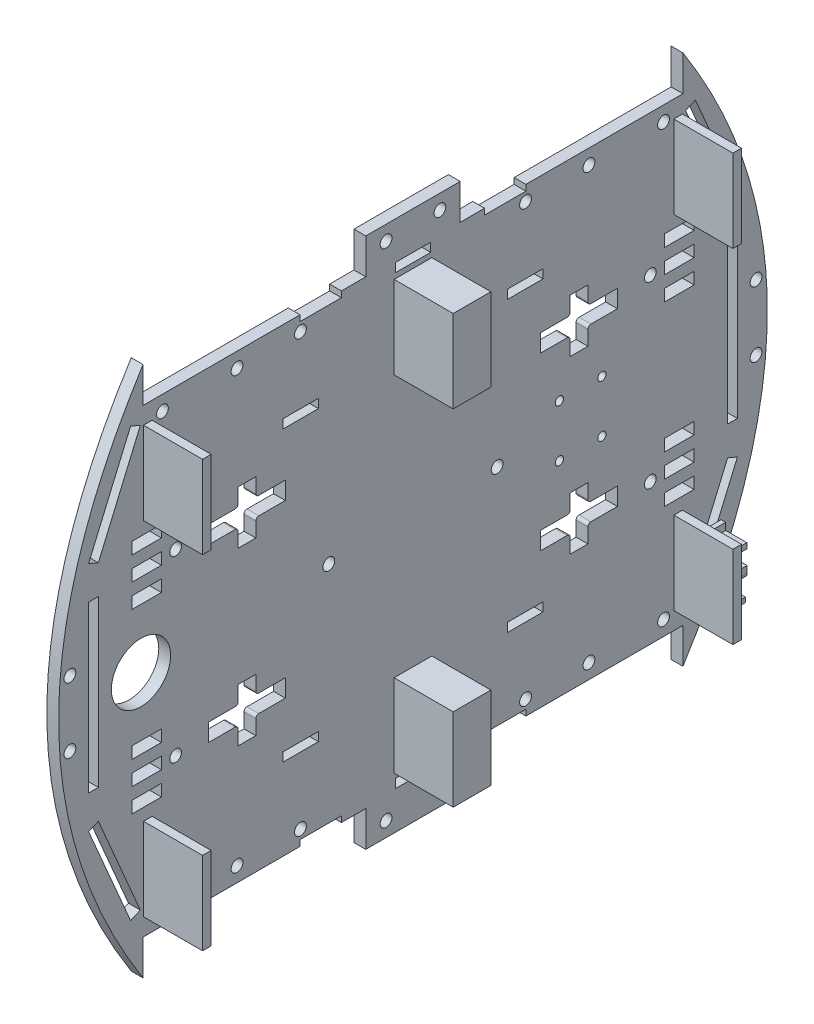
SolidWorks part; units mm, degrees
ref_plane "Front Plane" through (0, 0, 0) normal (0, 0, 1) x (1, 0, 0)
ref_plane "Top Plane" through (0, 0, 0) normal (0, 1, 0) x (1, 0, 0)
ref_plane "Right Plane" through (0, 0, 0) normal (1, 0, 0) x (0, 0, -1)
sketch "Sketch2" plane through (0, 0, 0) normal (1, 0, 0) x (0, 0, -1)
  line L0 (0, 0) -> (-14.2457, 0)
  line L1 (-120, 0) -> (-120, 90)
  line L2 (-120, 90) -> (-105.7002, 90)
  line L3 (0, 90) -> (0, 0)
  line L4 (-120, 45) -> (0, 45) construction
  line L5 (-59.9729, 90) -> (-59.9729, 0) construction
  line L6 (-105.7002, 90) -> (-105.7002, 84)
  line L7 (-105.7002, 84) -> (-79.1012, 84)
  line L8 (-14.2457, 90) -> (-14.2457, 84)
  line L9 (-14.2457, 0) -> (-14.2457, 6)
  line L10 (-105.7002, 6) -> (-79.1012, 6)
  line L11 (-105.7002, 0) -> (-105.7002, 6)
  line L12 (-67.9729, 84) -> (-67.9729, 90)
  line L13 (-67.9729, 90) -> (-51.9729, 90)
  line L14 (-51.9729, 90) -> (-51.9729, 84)
  line L15 (-51.9729, 0) -> (-51.9729, 6)
  line L16 (-120, 0) -> (-105.7002, 0)
  line L17 (-67.9729, 6) -> (-67.9729, 0)
  line L18 (-67.9729, 90) -> (-51.9729, 90)
  line L19 (-14.2457, 90) -> (0, 90)
  line L20 (-105.7002, 0) -> (-120, 0)
  line L21 (-67.9729, 0) -> (-51.9729, 0)
  line L22 (-51.9729, 0) -> (-67.9729, 0)
  line L23 (-14.2457, 0) -> (0, 0)
  line L24 (-51.9729, 6) -> (-47.8447, 6)
  line L25 (-51.9729, 84) -> (-47.8447, 84)
  line L26 (-72.1012, 84) -> (-72.1012, 83)
  line L27 (-72.1012, 83) -> (-79.1012, 83)
  line L28 (-79.1012, 83) -> (-79.1012, 84)
  line L29 (-47.8447, 84) -> (-47.8447, 83)
  line L30 (-47.8447, 83) -> (-40.8447, 83)
  line L31 (-40.8447, 83) -> (-40.8447, 84)
  line L32 (-40.8447, 7) -> (-40.8447, 6)
  line L33 (-47.8447, 7) -> (-40.8447, 7)
  line L34 (-47.8447, 6) -> (-47.8447, 7)
  line L35 (-79.1012, 7) -> (-79.1012, 6)
  line L36 (-72.1012, 7) -> (-79.1012, 7)
  line L37 (-72.1012, 6) -> (-72.1012, 7)
  line L38 (-72.1012, 84) -> (-67.9729, 84)
  line L39 (-40.8447, 84) -> (-14.2457, 84)
  line L40 (-72.1012, 6) -> (-67.9729, 6)
  line L41 (-40.8447, 6) -> (-14.2457, 6)
  spline S0 degree 2 poles (-14.2457, 90) (14.354, 45) (-14.2457, 0) knots 0 0 0 1 1 1
  spline S1 degree 2 poles (-105.7002, 90) (-134.2998, 45) (-105.7002, 0) knots 0 0 0 1 1 1
  point P17 (-59.9729, 84)
  dimension "D7" = 95.7362
  dimension "D1" = 120
  dimension "D2" = 90
  dimension "D3" = 8
  dimension "D4" = 8
  dimension "D5" = 6
  dimension "D6" = 1
  dimension "D8" = 7
extrude "Boss-Extrude1" add sketch "Sketch2" along normal blind 2 contours L6 S1 L11 L10 L35 L36 L37 L40 L17 L21 L15 L24 L34 L33 L32 L41 L9 S0 L3 L8 L39 L31 L30 L29 L25 L14 L13 L12 L38 L26 L27 L28 L7
sketch "Sketch3" plane through (2, 0, 0) normal (1, 0, 0) x (0, 0, -1)
  line L0 (-105.6201, 81.0571) -> (-105.6201, 67.0571)
  line L1 (-105.6201, 67.0571) -> (-104.1642, 67.0571)
  line L2 (-104.1642, 67.0571) -> (-104.1642, 81.0571)
  line L3 (-104.1642, 81.0571) -> (-105.6201, 81.0571)
  line L4 (-120, 45) -> (1.0597, 45) construction
  line L5 (-59.9729, 90) -> (-59.9729, 45) construction
  line L6 (-67.9729, 90) -> (-51.9729, 90) construction
  line L7 (-14.3257, 67.0571) -> (-15.7817, 67.0571)
  line L8 (-15.7817, 81.0571) -> (-14.3257, 81.0571)
  line L9 (-15.7817, 67.0571) -> (-15.7817, 81.0571)
  line L10 (-14.3257, 81.0571) -> (-14.3257, 67.0571)
  line L11 (-14.3257, 8.9429) -> (-14.3257, 22.9429)
  line L12 (-15.7817, 22.9429) -> (-15.7817, 8.9429)
  line L13 (-15.7817, 8.9429) -> (-14.3257, 8.9429)
  line L14 (-14.3257, 22.9429) -> (-15.7817, 22.9429)
  line L15 (-104.1642, 8.9429) -> (-105.6201, 8.9429)
  line L16 (-104.1642, 22.9429) -> (-104.1642, 8.9429)
  line L17 (-105.6201, 22.9429) -> (-104.1642, 22.9429)
  line L18 (-105.6201, 8.9429) -> (-105.6201, 22.9429)
  parabola Q0 (-105.7002, 90) -> (-105.7002, 0) focus (-84.5975, 45) apex (-120, 45) construction
  dimension "D1" = 14
extrude "Boss-Extrude2" add sketch "Sketch3" along normal blind 10
sketch "Sketch5" plane through (2, 0, 0) normal (1, 0, 0) x (0, 0, -1)
  line L0 (-56.7817, 8.7817) -> (-63.1642, 8.7817)
  line L1 (-63.1642, 8.7817) -> (-63.1642, 22.7817)
  line L2 (-63.1642, 22.7817) -> (-56.7817, 22.7817)
  line L3 (-56.7817, 22.7817) -> (-56.7817, 8.7817)
  line L4 (-104.1642, 8.9429) -> (-104.1642, 22.9429) construction
  line L5 (-15.7817, 22.9429) -> (-15.7817, 8.9429) construction
  line L6 (0, 45) -> (-130.9213, 45) construction
  line L7 (0, 47.7682) -> (0, 42.2318) construction
  line L14 (-56.7817, 67.2183) -> (-56.7817, 81.2183)
  line L15 (-63.1642, 67.2183) -> (-56.7817, 67.2183)
  line L16 (-63.1642, 81.2183) -> (-63.1642, 67.2183)
  line L17 (-56.7817, 81.2183) -> (-63.1642, 81.2183)
  dimension "D1" = 41
  dimension "D2" = 41
  dimension "D3" = 14
extrude "Boss-Extrude3" add sketch "Sketch5" along normal blind 10
sketch "Sketch6" plane through (0, 0, 0) normal (1, 0, 0) x (0, 0, -1)
  line L0 (-59.9729, 90) -> (-59.9729, 0) construction
  line L1 (-67.9729, 90) -> (-51.9729, 90) construction
  line L2 (-67.9729, 0) -> (-51.9729, 0) construction
  line L3 (0, 45) -> (-120, 45) construction
  line L4 (0, 47.7682) -> (0, 42.2318) construction
  line L5 (-88.1012, 84) -> (-88.1012, 69.2326) construction
  line L6 (-105.7002, 84) -> (-79.1012, 84) construction
  line L7 (-86.6012, 64) -> (-89.6012, 64)
  line L8 (-89.6012, 64) -> (-89.6012, 61.5)
  line L9 (-90.1012, 61) -> (-94.6012, 61)
  line L10 (-81.6012, 59.5) -> (-100.8376, 59.5) construction
  line L11 (-90.1012, 58) -> (-94.6012, 58)
  line L12 (-89.6012, 55) -> (-89.6012, 57.5)
  line L13 (-86.6012, 55) -> (-89.6012, 55)
  line L14 (-81.6012, 58) -> (-86.1012, 58)
  line L15 (-94.6012, 61) -> (-94.6012, 58)
  line L16 (-81.6012, 58) -> (-81.6012, 61)
  line L17 (-81.6012, 61) -> (-86.1012, 61)
  line L18 (-86.6012, 61.5) -> (-86.6012, 64)
  line L19 (-79.1012, 83) -> (-79.1012, 84) construction
  line L20 (-86.6012, 57.5) -> (-86.6012, 55)
  line L21 (-33.3447, 57.5) -> (-33.3447, 55)
  line L22 (-33.3447, 61.5) -> (-33.3447, 64)
  line L23 (-38.3447, 61) -> (-33.8447, 61)
  line L24 (-38.3447, 58) -> (-38.3447, 61)
  line L25 (-25.3447, 61) -> (-25.3447, 58)
  line L26 (-38.3447, 58) -> (-33.8447, 58)
  line L27 (-33.3447, 55) -> (-30.3447, 55)
  line L28 (-30.3447, 55) -> (-30.3447, 57.5)
  line L29 (-29.8447, 58) -> (-25.3447, 58)
  line L30 (-29.8447, 61) -> (-25.3447, 61)
  line L31 (-30.3447, 64) -> (-30.3447, 61.5)
  line L32 (-33.3447, 64) -> (-30.3447, 64)
  line L33 (-86.6012, 32.5) -> (-86.6012, 35)
  line L34 (-86.6012, 28.5) -> (-86.6012, 26)
  line L35 (-81.6012, 29) -> (-86.1012, 29)
  line L36 (-81.6012, 32) -> (-81.6012, 29)
  line L37 (-94.6012, 29) -> (-94.6012, 32)
  line L38 (-81.6012, 32) -> (-86.1012, 32)
  line L39 (-86.6012, 35) -> (-89.6012, 35)
  line L40 (-89.6012, 35) -> (-89.6012, 32.5)
  line L41 (-90.1012, 32) -> (-94.6012, 32)
  line L42 (-90.1012, 29) -> (-94.6012, 29)
  line L43 (-89.6012, 26) -> (-89.6012, 28.5)
  line L44 (-86.6012, 26) -> (-89.6012, 26)
  line L45 (-33.3447, 26) -> (-30.3447, 26)
  line L46 (-30.3447, 26) -> (-30.3447, 28.5)
  line L47 (-29.8447, 29) -> (-25.3447, 29)
  line L48 (-29.8447, 32) -> (-25.3447, 32)
  line L49 (-30.3447, 35) -> (-30.3447, 32.5)
  line L50 (-33.3447, 35) -> (-30.3447, 35)
  line L51 (-38.3447, 32) -> (-33.8447, 32)
  line L52 (-25.3447, 29) -> (-25.3447, 32)
  line L53 (-38.3447, 32) -> (-38.3447, 29)
  line L54 (-38.3447, 29) -> (-33.8447, 29)
  line L55 (-33.3447, 28.5) -> (-33.3447, 26)
  line L56 (-33.3447, 32.5) -> (-33.3447, 35)
  circle A0 centre (-106.0549, 45) radius 5.019
  arc A1 (-89.6012, 61.5) -> (-90.1012, 61) centre (-90.1012, 61.5) cw
  arc A2 (-90.1012, 58) -> (-89.6012, 57.5) centre (-90.1012, 57.5) cw
  arc A3 (-86.1012, 58) -> (-86.6012, 57.5) centre (-86.1012, 57.5) ccw
  arc A4 (-86.1012, 61) -> (-86.6012, 61.5) centre (-86.1012, 61.5) cw
  arc A5 (-33.8447, 61) -> (-33.3447, 61.5) centre (-33.8447, 61.5) ccw
  arc A6 (-33.8447, 58) -> (-33.3447, 57.5) centre (-33.8447, 57.5) cw
  arc A7 (-29.8447, 58) -> (-30.3447, 57.5) centre (-29.8447, 57.5) ccw
  arc A8 (-30.3447, 61.5) -> (-29.8447, 61) centre (-29.8447, 61.5) ccw
  arc A9 (-86.1012, 29) -> (-86.6012, 28.5) centre (-86.1012, 28.5) ccw
  arc A10 (-86.1012, 32) -> (-86.6012, 32.5) centre (-86.1012, 32.5) cw
  arc A11 (-90.1012, 32) -> (-89.6012, 32.5) centre (-90.1012, 32.5) ccw
  arc A12 (-89.6012, 28.5) -> (-90.1012, 29) centre (-90.1012, 28.5) ccw
  arc A13 (-30.3447, 28.5) -> (-29.8447, 29) centre (-29.8447, 28.5) cw
  arc A14 (-29.8447, 32) -> (-30.3447, 32.5) centre (-29.8447, 32.5) cw
  arc A15 (-33.8447, 32) -> (-33.3447, 32.5) centre (-33.8447, 32.5) ccw
  arc A16 (-33.8447, 29) -> (-33.3447, 28.5) centre (-33.8447, 28.5) cw
  circle A17 centre (-13.891, 45) radius 5.019
  parabola Q0 (-105.7002, 90) -> (-105.7002, 0) focus (-84.5975, 45) apex (-120, 45) construction
  point P38 (-89.6012, 61)
  point P41 (-89.6012, 58)
  point P44 (-86.6012, 58)
  point P47 (-86.6012, 61)
  point P68 (-33.3447, 61)
  point P69 (-33.3447, 58)
  point P70 (-30.3447, 58)
  point P71 (-30.3447, 61)
  point P92 (-86.6012, 29)
  point P93 (-86.6012, 32)
  point P94 (-89.6012, 32)
  point P95 (-89.6012, 29)
  point P116 (-30.3447, 29)
  point P117 (-30.3447, 32)
  point P118 (-33.3447, 32)
  point P119 (-33.3447, 29)
  dimension "D6" = 0.5
  dimension "D1" = 20
  dimension "D2" = 1.5
  dimension "D3" = 1.5
  dimension "D4" = 9
  dimension "D5" = 5
  dimension "D8" = 3
  dimension "D9" = 3
  dimension "D10" = 5
  dimension "D11" = 3
extrude "Cut-Extrude5" cut sketch "Sketch6" along normal blind 24
sketch "Sketch7" plane through (0, 0, 0) normal (1, 0, 0) x (0, 0, -1)
  line L0 (-107.8144, 82.0133) -> (-114.9272, 65.4166)
  line L1 (-114.9272, 65.4166) -> (-113.2739, 64.708)
  line L2 (-113.2739, 64.708) -> (-106.1611, 81.3048)
  line L3 (-106.1611, 81.3048) -> (-107.8144, 82.0133)
  line L4 (-114.9272, 59.7526) -> (-114.9272, 31.7526)
  line L5 (-114.9272, 31.7526) -> (-113.2739, 31.7526)
  line L6 (-113.2739, 31.7526) -> (-113.2739, 59.7526)
  line L7 (-113.2739, 59.7526) -> (-114.9272, 59.7526)
  line L8 (-119.996, 45.7526) -> (35.8922, 45.7526) construction
  line L9 (-107.8144, 9.492) -> (-114.9272, 26.0887)
  line L10 (-113.2739, 26.7972) -> (-106.1611, 10.2005)
  line L11 (-113.2739, 26.7972) -> (-114.9272, 26.0887)
  line L12 (-107.8144, 9.492) -> (-106.1611, 10.2005)
  line L13 (-59.9729, 90) -> (-59.9729, 70.4012) construction
  line L14 (-67.9729, 90) -> (-51.9729, 90) construction
  line L15 (-6.6719, 26.7972) -> (-13.7848, 10.2005)
  line L16 (-12.1315, 9.492) -> (-5.0186, 26.0887)
  line L17 (-5.0186, 59.7526) -> (-5.0186, 31.7526)
  line L18 (-6.6719, 31.7526) -> (-6.6719, 59.7526)
  line L19 (-12.1315, 82.0133) -> (-5.0186, 65.4166)
  line L20 (-6.6719, 64.708) -> (-13.7848, 81.3048)
  line L21 (-12.1315, 82.0133) -> (-13.7848, 81.3048)
  line L22 (-5.0186, 65.4166) -> (-6.6719, 64.708)
  line L23 (-5.0186, 59.7526) -> (-6.6719, 59.7526)
  line L24 (-5.0186, 26.0887) -> (-6.6719, 26.7972)
  line L25 (-12.1315, 9.492) -> (-13.7848, 10.2005)
  line L26 (-6.6719, 31.7526) -> (-5.0186, 31.7526)
  parabola Q0 (-105.7002, 90) -> (-105.7002, 0) focus (-84.5975, 45) apex (-120, 45) construction
  point P14 (-114.1006, 59.7526)
  dimension "D1" = 14
  dimension "D2" = 14
extrude "Cut-Extrude6" cut sketch "Sketch7" along normal blind 41
sketch "Sketch9" plane through (0, 0, 0) normal (1, 0, 0) x (0, 0, -1)
  line L0 (-59.9729, 90) -> (-59.9729, 25.6471) construction
  line L1 (-67.9729, 90) -> (-51.9729, 90) construction
  line L2 (0, 45) -> (-59.9729, 45) construction
  line L3 (0, 47.7682) -> (0, 42.2318) construction
  line L4 (-12.3575, 55) -> (-17.3575, 55)
  line L5 (-17.3575, 55) -> (-17.3575, 57)
  line L6 (-17.3575, 57) -> (-12.3575, 57)
  line L7 (-12.3575, 57) -> (-12.3575, 55)
  line L8 (-12.3552, 59) -> (-17.3575, 59)
  line L9 (-17.3575, 59) -> (-17.3575, 61)
  line L10 (-17.3575, 61) -> (-12.3552, 61)
  line L11 (-12.3552, 61) -> (-12.3552, 59)
  line L12 (-12.3552, 63) -> (-17.3575, 63)
  line L13 (-17.3575, 63) -> (-17.3575, 65)
  line L14 (-17.3575, 65) -> (-12.3552, 65)
  line L15 (-12.3552, 65) -> (-12.3552, 63)
  line L16 (-12.3552, 25) -> (-12.3552, 27)
  line L17 (-17.3575, 25) -> (-12.3552, 25)
  line L18 (-17.3575, 27) -> (-17.3575, 25)
  line L19 (-12.3552, 27) -> (-17.3575, 27)
  line L20 (-12.3552, 29) -> (-12.3552, 31)
  line L21 (-17.3575, 29) -> (-12.3552, 29)
  line L22 (-17.3575, 31) -> (-17.3575, 29)
  line L23 (-12.3552, 31) -> (-17.3575, 31)
  line L24 (-12.3575, 33) -> (-12.3575, 35)
  line L25 (-17.3575, 33) -> (-12.3575, 33)
  line L26 (-17.3575, 35) -> (-17.3575, 33)
  line L27 (-12.3575, 35) -> (-17.3575, 35)
  line L28 (-107.5884, 35) -> (-102.5884, 35)
  line L29 (-102.5884, 35) -> (-102.5884, 33)
  line L30 (-102.5884, 33) -> (-107.5884, 33)
  line L31 (-107.5884, 33) -> (-107.5884, 35)
  line L32 (-107.5907, 31) -> (-102.5884, 31)
  line L33 (-102.5884, 31) -> (-102.5884, 29)
  line L34 (-102.5884, 29) -> (-107.5907, 29)
  line L35 (-107.5907, 29) -> (-107.5907, 31)
  line L36 (-107.5907, 27) -> (-102.5884, 27)
  line L37 (-102.5884, 27) -> (-102.5884, 25)
  line L38 (-102.5884, 25) -> (-107.5907, 25)
  line L39 (-107.5907, 25) -> (-107.5907, 27)
  line L40 (-107.5907, 65) -> (-107.5907, 63)
  line L41 (-102.5884, 65) -> (-107.5907, 65)
  line L42 (-102.5884, 63) -> (-102.5884, 65)
  line L43 (-107.5907, 63) -> (-102.5884, 63)
  line L44 (-107.5907, 61) -> (-107.5907, 59)
  line L45 (-102.5884, 61) -> (-107.5907, 61)
  line L46 (-102.5884, 59) -> (-102.5884, 61)
  line L47 (-107.5907, 59) -> (-102.5884, 59)
  line L48 (-107.5884, 57) -> (-107.5884, 55)
  line L49 (-102.5884, 57) -> (-107.5884, 57)
  line L50 (-102.5884, 55) -> (-102.5884, 57)
  line L51 (-107.5884, 55) -> (-102.5884, 55)
  dimension "D1" = 10
  dimension "D2" = 5
  dimension "D3" = 2
  dimension "D4" = 2
  dimension "D5" = 5.0022
  dimension "D6" = 2
  dimension "D7" = 5.0022
  dimension "D8" = 2
  dimension "D9" = 2
extrude "Cut-Extrude7" cut sketch "Sketch9" along normal blind 55
sketch "Sketch10" plane through (0, 0, 0) normal (1, 0, 0) x (0, 0, -1)
  line L0 (-59.9729, 90) -> (-59.9729, 0) construction
  line L1 (-67.9729, 90) -> (-51.9729, 90) construction
  line L2 (-67.9729, 0) -> (-51.9729, 0) construction
  line L3 (0, 45) -> (-120, 45) construction
  line L4 (0, 47.7682) -> (0, 42.2318) construction
  line L5 (-56.9729, 83.5885) -> (-62.9729, 83.5885)
  line L6 (-62.9729, 83.5885) -> (-62.9729, 82.0885)
  line L7 (-62.9729, 82.0885) -> (-56.9729, 82.0885)
  line L8 (-56.9729, 82.0885) -> (-56.9729, 83.5885)
  line L9 (-37.9521, 70.1825) -> (-37.9521, 68.6825)
  line L10 (-37.9521, 68.6825) -> (-43.9521, 68.6825)
  line L11 (-43.9521, 68.6825) -> (-43.9521, 70.1825)
  line L12 (-43.9521, 70.1825) -> (-37.9521, 70.1825)
  line L13 (-75.9938, 70.1825) -> (-81.9938, 70.1825)
  line L14 (-75.9938, 68.6825) -> (-75.9938, 70.1825)
  line L15 (-81.9938, 68.6825) -> (-75.9938, 68.6825)
  line L16 (-81.9938, 70.1825) -> (-81.9938, 68.6825)
  line L17 (-81.9938, 19.8175) -> (-81.9938, 21.3175)
  line L18 (-81.9938, 21.3175) -> (-75.9938, 21.3175)
  line L19 (-75.9938, 21.3175) -> (-75.9938, 19.8175)
  line L20 (-75.9938, 19.8175) -> (-81.9938, 19.8175)
  line L21 (-56.9729, 7.9115) -> (-56.9729, 6.4115)
  line L22 (-62.9729, 7.9115) -> (-56.9729, 7.9115)
  line L23 (-62.9729, 6.4115) -> (-62.9729, 7.9115)
  line L24 (-56.9729, 6.4115) -> (-62.9729, 6.4115)
  line L25 (-43.9521, 19.8175) -> (-37.9521, 19.8175)
  line L26 (-43.9521, 21.3175) -> (-43.9521, 19.8175)
  line L27 (-37.9521, 21.3175) -> (-43.9521, 21.3175)
  line L28 (-37.9521, 19.8175) -> (-37.9521, 21.3175)
  circle A0 centre (-102.4138, 81.4864) radius 1
  circle A1 centre (-100.1746, 60.1478) radius 1
  circle A2 centre (-74.2258, 45) radius 1
  circle A3 centre (-118.0885, 50.5322) radius 1
  circle A4 centre (-1.8574, 50.5322) radius 1
  circle A5 centre (-19.7713, 60.1478) radius 1
  circle A6 centre (-17.532, 81.4864) radius 1
  circle A7 centre (-118.0885, 39.4678) radius 1
  circle A8 centre (-102.4138, 8.5136) radius 1
  circle A9 centre (-100.1746, 29.8522) radius 1
  circle A10 centre (-1.8574, 39.4678) radius 1
  circle A11 centre (-19.7713, 29.8522) radius 1
  circle A12 centre (-17.532, 8.5136) radius 1
  circle A13 centre (-45.7201, 45) radius 1
  circle A14 centre (-64.53, 87.5003) radius 1
  circle A15 centre (-30.1681, 81.4864) radius 1
  circle A16 centre (-64.53, 2.4997) radius 1
  circle A17 centre (-40.9068, 81.4864) radius 1
  circle A18 centre (-55.4159, 2.4997) radius 1
  circle A19 centre (-55.4159, 87.5003) radius 1
  circle A20 centre (-79.0391, 81.4864) radius 1
  circle A21 centre (-89.7778, 81.4864) radius 1
  circle A22 centre (-89.7778, 8.5136) radius 1
  circle A23 centre (-79.0391, 8.5136) radius 1
  circle A24 centre (-30.1681, 8.5136) radius 1
  circle A25 centre (-40.9068, 8.5136) radius 1
  parabola Q0 (-105.7002, 90) -> (-105.7002, 0) focus (-84.5975, 45) apex (-120, 45) construction
  dimension "D1" = 2
  dimension "D2" = 2
  dimension "D3" = 2
  dimension "D4" = 2
  dimension "D5" = 6
  dimension "D6" = 2
  dimension "D11" = 2
  dimension "D12" = 2
  dimension "D7" = 3
  dimension "D8" = 6
  dimension "D9" = 1.5
  dimension "D10" = 1.5
extrude "Cut-Extrude8" cut sketch "Sketch10" along normal blind 80
sketch "Sketch11" plane through (0, 0, 0) normal (1, 0, 0) x (0, 0, -1)
  line L0 (-120, 45) -> (1.5828, 45) construction
  line L1 (-40.4174, 78.6375) -> (-40.4174, 71.6375)
  line L2 (-40.4174, 71.6375) -> (-22.4174, 71.6375)
  line L3 (-22.4174, 71.6375) -> (-22.4174, 78.6375)
  line L4 (-22.4174, 78.6375) -> (-40.4174, 78.6375)
  line L5 (-22.4174, 11.3625) -> (-40.4174, 11.3625)
  line L6 (-22.4174, 18.3625) -> (-22.4174, 11.3625)
  line L7 (-40.4174, 18.3625) -> (-22.4174, 18.3625)
  line L8 (-40.4174, 11.3625) -> (-40.4174, 18.3625)
  parabola Q0 (-105.7002, 90) -> (-105.7002, 0) focus (-84.5975, 45) apex (-120, 45) construction
  dimension "D1" = 7
  dimension "D2" = 18
sketch "Sketch13" plane through (2, 0, 0) normal (1, 0, 0) x (0, 0, -1)
  circle A0 centre (-13.891, 45) radius 5.019 construction
  circle A1 centre (-13.891, 45) radius 4.9083
  dimension "D1" = 9.8166
sketch "Sketch14" plane through (2, 0, 0) normal (1, 0, 0) x (0, 0, -1)
  circle A0 centre (-13.891, 45) radius 5.019
extrude "Boss-Extrude7" add sketch "Sketch14" against normal blind 2
sketch "Sketch15" plane through (0, 0, 0) normal (-1, 0, 0) x (0, 0, 1)
  line L0 (120, 45) -> (-1.5828, 45) construction
  circle A0 centre (27.9723, 49.4) radius 0.7
  circle A1 centre (35.1723, 49.4) radius 0.7
  circle A2 centre (27.9723, 40.6) radius 0.7
  circle A3 centre (35.1723, 40.6) radius 0.7
  dimension "D1" = 1.4
  dimension "D2" = 1.4
  dimension "D3" = 1.4
  dimension "D4" = 1.4
  dimension "D5" = 4.4
  dimension "D6" = 4.4
  dimension "D7" = 7.2
extrude "Cut-Extrude10" cut sketch "Sketch15" against normal blind 3
sketch "Sketch16" plane through (0, 0, 14.3257) normal (0, 0, -1) x (-1, 0, 0)
  line L0 (-9.9002, 19.7009) -> (-6.3239, 19.7009)
  line L1 (-6.3239, 19.7009) -> (-6.3239, 18.2223)
  line L2 (-6.3239, 18.2223) -> (-5.5642, 18.2223)
  line L3 (-5.5642, 18.2223) -> (-5.5642, 21.8329)
  line L4 (-5.5642, 21.8329) -> (-6.3239, 21.8329)
  line L5 (-6.3239, 21.8329) -> (-6.3239, 20.6294)
  line L6 (-6.3239, 20.6294) -> (-9.9002, 20.6294)
  line L7 (-9.9002, 20.6294) -> (-9.9002, 19.7009)
  line L8 (-9.9499, 17.3021) -> (-5.9575, 17.3021)
  line L9 (-5.9575, 17.3021) -> (-5.9575, 16.0865)
  line L10 (-9.9499, 17.3021) -> (-9.9499, 16.2394)
  line L11 (-7.9449, 16.1816) -> (-7.7525, 16.1816)
  line L12 (-9.2391, 16.692) -> (-8.4783, 16.692)
  line L13 (-8.4783, 16.692) -> (-8.4783, 16.2394)
  line L14 (-9.2391, 16.692) -> (-9.2391, 16.2394)
  line L15 (-7.0509, 16.692) -> (-6.3359, 16.692)
  line L16 (-6.3359, 16.692) -> (-6.3359, 16.3436)
  line L17 (-7.0509, 16.692) -> (-7.0509, 16.3436)
  line L18 (-5.5642, 13.9708) -> (-5.5642, 10.6682)
  line L19 (-5.5642, 10.6682) -> (-6.3359, 10.6682)
  line L20 (-6.3359, 10.6682) -> (-6.3359, 11.7295)
  line L21 (-6.3359, 11.7295) -> (-9.6811, 11.7295)
  line L22 (-9.6811, 11.7295) -> (-9.6811, 12.5323)
  line L23 (-9.6811, 12.5323) -> (-6.3359, 12.5323)
  line L24 (-6.3359, 12.5323) -> (-6.3359, 13.9708)
  line L25 (-6.3359, 13.9708) -> (-5.5642, 13.9708)
  arc A0 (-9.9499, 16.2394) -> (-7.9449, 16.1816) centre (-8.9466, 16.2394) ccw
  arc A1 (-5.9575, 16.0865) -> (-7.7525, 16.1816) centre (-6.8575, 16.0865) cw
  arc A2 (-8.4783, 16.2394) -> (-9.2391, 16.2394) centre (-8.8587, 16.2394) cw
  arc A3 (-7.0509, 16.3436) -> (-6.3359, 16.3436) centre (-6.6934, 16.3436) ccw
  point P34 (-5.5642, 13.9702)
  point P35 (-8.0111, 16.0665)
  point P36 (-5.6288, 13.975)
  point P37 (-7.9433, 16.2283)
  point P38 (-7.7525, 16.1816)
  dimension "D1" = 0.9
extrude "Boss-Extrude9" add sketch "Sketch16" along normal blind 3
